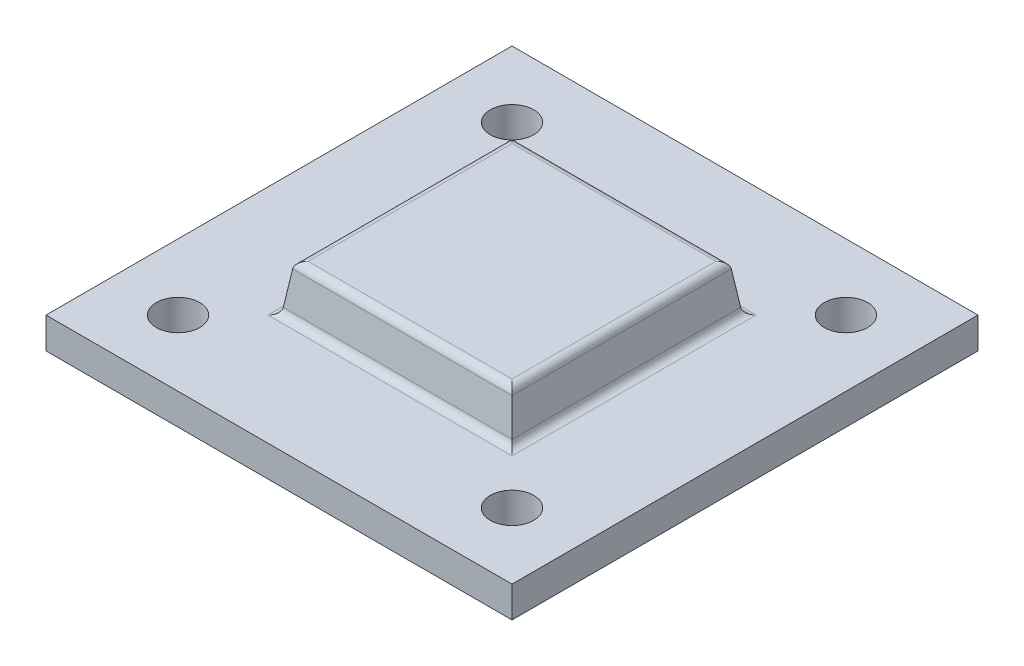
SolidWorks part; units mm, degrees
material "Nylon 101"
ref_plane "Front Plane" through (0, 0, 0) normal (0, 0, 1) x (1, 0, 0)
ref_plane "Top Plane" through (0, 0, 0) normal (0, 1, 0) x (1, 0, 0)
ref_plane "Right Plane" through (0, 0, 0) normal (1, 0, 0) x (0, 0, -1)
sketch "Sketch1" plane through (0, 0, 0) normal (0, 1, 0) x (1, 0, 0)
  line L1 (-30, -30) -> (30, -30)
  line L2 (-30, -30) -> (-30, 30)
  line L3 (-30, 30) -> (30, 30)
  line L4 (30, -30) -> (30, 30)
  line L5 (-30, -30) -> (30, 30) construction
  line L6 (-30, 30) -> (30, -30) construction
  point P0 (0, 0)
  dimension "D1" = 60
  dimension "D2" = 60
extrude "Boss-Extrude1" add sketch "Sketch1" along normal blind 4
sketch "Sketch2" plane through (0, 4, 0) normal (0, 1, 0) x (1, 0, 0)
  line L1 (-14, -14) -> (14, -14)
  line L2 (-14, -14) -> (-14, 14)
  line L3 (-14, 14) -> (14, 14)
  line L4 (14, -14) -> (14, 14)
  line L5 (-14, -14) -> (14, 14) construction
  line L6 (-14, 14) -> (14, -14) construction
  point P0 (0, 0)
  dimension "D1" = 28
  dimension "D2" = 28
extrude "Boss-Extrude2" add sketch "Sketch2" along normal blind 6
draft "Draft1" type of draft neutral plane draft angle 8 faces to draft 4 face at (-14, 7, 0) face at (0, 7, -14) face at (14, 7, 0) face at (0, 7, 14) neutral plane through (0, 10, 0) neutral plane normal (0, 1, 0) parameters "D1"=8
fillet "Fillet1" radius 1 8 edges at (0, 10, 14) (-14, 10, 0) (0, 10, -14) (14, 10, 0) (0, 4, 14.8432) (-14.8432, 4, 0) (0, 4, -14.8432) (14.8432, 4, 0)
sketch "Sketch3" plane through (0, 4, 0) normal (0, 1, 0) x (1, 0, 0)
  line L0 (-44.1749, 0) -> (43.8775, 0) construction
  line L1 (0, 43.1576) -> (0, -46.5845) construction
  circle A0 centre (-21.5, 21.5) radius 2.794
  circle A1 centre (21.5, 21.5) radius 2.794
  circle A2 centre (21.5, -21.5) radius 2.794
  circle A3 centre (-21.5, -21.5) radius 2.794
  dimension "D1" = 5.588
  dimension "D2" = 21.5
  dimension "D3" = 21.5
extrude "Cut-Extrude1" cut sketch "Sketch3" against normal through all
